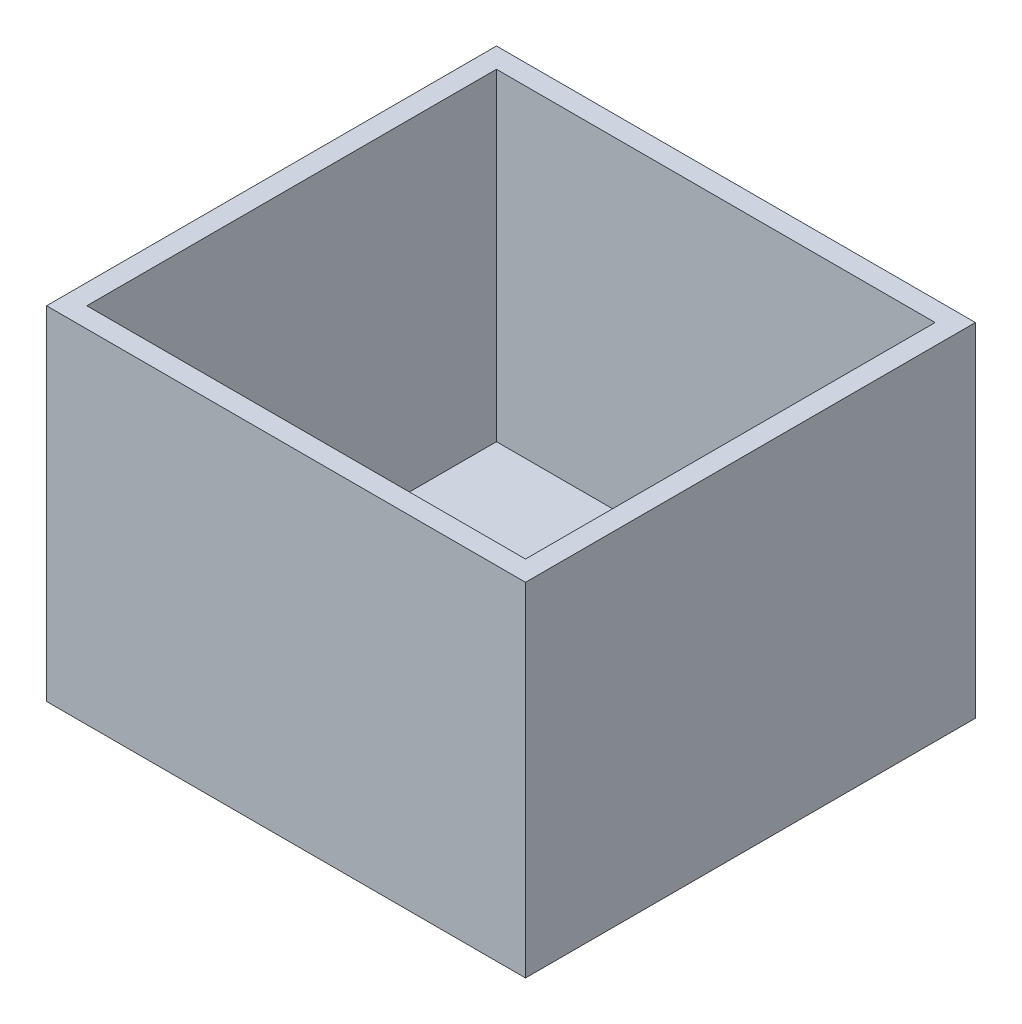
SolidWorks part; units mm, degrees
ref_plane "Front Plane" through (0, 0, 0) normal (0, 0, 1) x (1, 0, 0)
ref_plane "Top Plane" through (0, 0, 0) normal (0, 1, 0) x (1, 0, 0)
ref_plane "Right Plane" through (0, 0, 0) normal (1, 0, 0) x (0, 0, -1)
sketch "Sketch1" plane through (0, 0, 0) normal (0, 1, 0) x (1, 0, 0)
  line L1 (0, 0) -> (69.088, 0)
  line L2 (0, 0) -> (0, -64.516)
  line L3 (0, -64.516) -> (69.088, -64.516)
  line L4 (69.088, 0) -> (69.088, -64.516)
  dimension "D1" = 64.516
  dimension "D2" = 69.088
extrude "Boss-Extrude1" add sketch "Sketch1" along normal blind 50.8
shell "Shell1" thickness 3.175
sketch "Sketch2" plane through (0, 0, 0) normal (0, 1, 0) x (1, 0, 0)
  line L0 (0, 0) -> (0, -64.516) construction
  line L1 (0, -64.516) -> (69.088, -64.516) construction
  circle A0 centre (14.478, -61.468) radius 1.905
  dimension "D3" = 3.81
  dimension "D1" = 14.478
  dimension "D2" = 3.048
